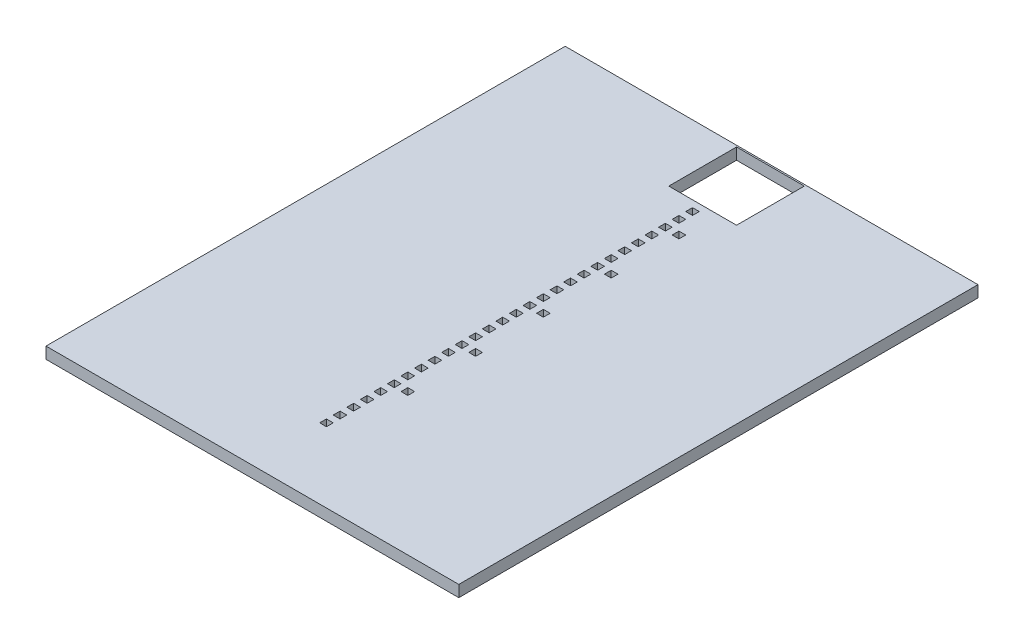
SolidWorks part; units mm, degrees
ref_plane "Front Plane" through (0, 0, 0) normal (0, 0, 1) x (1, 0, 0)
ref_plane "Top Plane" through (0, 0, 0) normal (0, 1, 0) x (1, 0, 0)
ref_plane "Right Plane" through (0, 0, 0) normal (1, 0, 0) x (0, 0, -1)
sketch "Sketch1" plane through (0, 0, 0) normal (0, 1, 0) x (1, 0, 0)
  line L0 (-5, -90) -> (5, -90)
  line L1 (-305, 52.21) -> (304, 52.21)
  line L2 (-305, 52.21) -> (-305, -713.79)
  line L3 (-305, -713.79) -> (304, -713.79)
  line L4 (304, 52.21) -> (304, -713.79)
  line L5 (-50, 50) -> (50, 50)
  line L6 (-50, 50) -> (-50, -50)
  line L7 (-50, -50) -> (50, -50)
  line L8 (50, 50) -> (50, -50)
  line L9 (-5, -60) -> (5, -60)
  line L10 (-5, -60) -> (-5, -70)
  line L11 (-5, -70) -> (5, -70)
  line L12 (5, -60) -> (5, -70)
  line L13 (5, -80) -> (5, -90)
  line L14 (-5, -80) -> (5, -80)
  line L15 (-5, -80) -> (-5, -90)
  line L16 (-5, -110) -> (5, -110)
  line L17 (5, -100) -> (5, -110)
  line L18 (-5, -100) -> (5, -100)
  line L19 (-5, -100) -> (-5, -110)
  line L20 (-5, -130) -> (5, -130)
  line L21 (5, -120) -> (5, -130)
  line L22 (-5, -120) -> (5, -120)
  line L23 (-5, -120) -> (-5, -130)
  line L24 (-5, -150) -> (5, -150)
  line L25 (5, -140) -> (5, -150)
  line L26 (-5, -140) -> (5, -140)
  line L27 (-5, -140) -> (-5, -150)
  line L28 (-5, -170) -> (5, -170)
  line L29 (5, -160) -> (5, -170)
  line L30 (-5, -160) -> (5, -160)
  line L31 (-5, -160) -> (-5, -170)
  line L32 (-5, -190) -> (5, -190)
  line L33 (5, -180) -> (5, -190)
  line L34 (-5, -180) -> (5, -180)
  line L35 (-5, -180) -> (-5, -190)
  line L36 (-5, -210) -> (5, -210)
  line L37 (5, -200) -> (5, -210)
  line L38 (-5, -200) -> (5, -200)
  line L39 (-5, -200) -> (-5, -210)
  line L40 (-5, -230) -> (5, -230)
  line L41 (5, -220) -> (5, -230)
  line L42 (-5, -220) -> (5, -220)
  line L43 (-5, -220) -> (-5, -230)
  line L44 (-5, -250) -> (5, -250)
  line L45 (5, -240) -> (5, -250)
  line L46 (-5, -240) -> (5, -240)
  line L47 (-5, -240) -> (-5, -250)
  line L48 (-5, -270) -> (5, -270)
  line L49 (5, -260) -> (5, -270)
  line L50 (-5, -260) -> (5, -260)
  line L51 (-5, -260) -> (-5, -270)
  line L52 (-5, -290) -> (5, -290)
  line L53 (5, -280) -> (5, -290)
  line L54 (-5, -280) -> (5, -280)
  line L55 (-5, -280) -> (-5, -290)
  line L56 (-5, -310) -> (5, -310)
  line L57 (5, -300) -> (5, -310)
  line L58 (-5, -300) -> (5, -300)
  line L59 (-5, -300) -> (-5, -310)
  line L60 (-5, -330) -> (5, -330)
  line L61 (5, -320) -> (5, -330)
  line L62 (-5, -320) -> (5, -320)
  line L63 (-5, -320) -> (-5, -330)
  line L64 (-5, -350) -> (5, -350)
  line L65 (5, -340) -> (5, -350)
  line L66 (-5, -340) -> (5, -340)
  line L67 (-5, -340) -> (-5, -350)
  line L68 (-5, -370) -> (5, -370)
  line L69 (5, -360) -> (5, -370)
  line L70 (-5, -360) -> (5, -360)
  line L71 (-5, -360) -> (-5, -370)
  line L72 (-5, -390) -> (5, -390)
  line L73 (5, -380) -> (5, -390)
  line L74 (-5, -380) -> (5, -380)
  line L75 (-5, -380) -> (-5, -390)
  line L76 (-5, -410) -> (5, -410)
  line L77 (5, -400) -> (5, -410)
  line L78 (-5, -400) -> (5, -400)
  line L79 (-5, -400) -> (-5, -410)
  line L80 (-5, -430) -> (5, -430)
  line L81 (5, -420) -> (5, -430)
  line L82 (-5, -420) -> (5, -420)
  line L83 (-5, -420) -> (-5, -430)
  line L84 (-5, -450) -> (5, -450)
  line L85 (5, -440) -> (5, -450)
  line L86 (-5, -440) -> (5, -440)
  line L87 (-5, -440) -> (-5, -450)
  line L88 (-5, -470) -> (5, -470)
  line L89 (5, -460) -> (5, -470)
  line L90 (-5, -460) -> (5, -460)
  line L91 (-5, -460) -> (-5, -470)
  line L92 (-5, -490) -> (5, -490)
  line L93 (5, -480) -> (5, -490)
  line L94 (-5, -480) -> (5, -480)
  line L95 (-5, -480) -> (-5, -490)
  line L96 (-5, -510) -> (5, -510)
  line L97 (5, -500) -> (5, -510)
  line L98 (-5, -500) -> (5, -500)
  line L99 (-5, -500) -> (-5, -510)
  line L100 (-5, -530) -> (5, -530)
  line L101 (5, -520) -> (5, -530)
  line L102 (-5, -520) -> (5, -520)
  line L103 (-5, -520) -> (-5, -530)
  line L104 (-5, -550) -> (5, -550)
  line L105 (5, -540) -> (5, -550)
  line L106 (-5, -540) -> (5, -540)
  line L107 (-5, -540) -> (-5, -550)
  line L108 (-5, -570) -> (5, -570)
  line L109 (5, -560) -> (5, -570)
  line L110 (-5, -560) -> (5, -560)
  line L111 (-5, -560) -> (-5, -570)
  line L112 (-5, -590) -> (5, -590)
  line L113 (5, -580) -> (5, -590)
  line L114 (-5, -580) -> (5, -580)
  line L115 (-5, -580) -> (-5, -590)
  line L116 (-5, -610) -> (5, -610)
  line L117 (5, -600) -> (5, -610)
  line L118 (-5, -600) -> (5, -600)
  line L119 (-5, -600) -> (-5, -610)
  line L121 (15, -100) -> (25, -100)
  line L122 (15, -100) -> (15, -110)
  line L123 (25, -100) -> (25, -110)
  line L124 (15, -110) -> (25, -110)
  line L125 (15, -200) -> (25, -200)
  line L126 (15, -200) -> (15, -210)
  line L127 (15, -210) -> (25, -210)
  line L128 (25, -200) -> (25, -210)
  line L129 (15, -300) -> (25, -300)
  line L130 (15, -300) -> (15, -310)
  line L131 (25, -300) -> (25, -310)
  line L132 (15, -310) -> (25, -310)
  line L133 (15, -400) -> (25, -400)
  line L134 (25, -400) -> (25, -410)
  line L135 (15, -410) -> (25, -410)
  line L136 (15, -400) -> (15, -410)
  line L137 (15, -500) -> (25, -500)
  line L138 (25, -500) -> (25, -510)
  line L139 (15, -510) -> (25, -510)
  line L140 (15, -500) -> (15, -510)
  dimension "D1" = 609
  dimension "D2" = 766
  dimension "D3" = 100
  dimension "D4" = 100
  dimension "D5" = 50
  dimension "D6" = 50
  dimension "D7" = 2.21
  dimension "D8" = 255
  dimension "D9" = 10
  dimension "D10" = 10
  dimension "D11" = 60
  dimension "D12" = 5
  dimension "D14" = 80
  dimension "D15" = 2
  dimension "D16" = 100
  dimension "D17" = 10
  dimension "D19" = 100
  dimension "D20" = 10
  dimension "D22" = 100
  dimension "D23" = 10
  dimension "D24" = 2
  dimension "D25" = 100
  dimension "D26" = 10
  dimension "D28" = 100
  dimension "D29" = 10
  dimension "D13" = 28
  dimension "D18" = 2
  dimension "D21" = 2
  dimension "D27" = 2
extrude "Boss-Extrude1" add sketch "Sketch1" along normal blind 17
